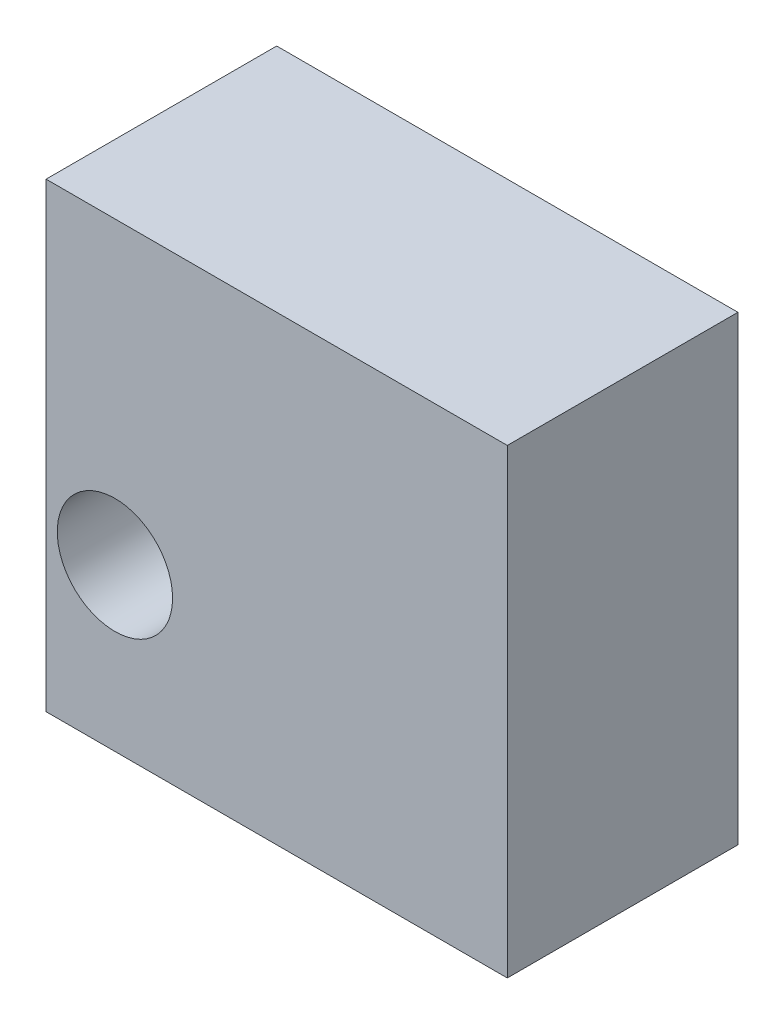
SolidWorks part; units mm, degrees
ref_plane "前视基准面" through (0, 0, 0) normal (0, 0, 1) x (1, 0, 0)
ref_plane "上视基准面" through (0, 0, 0) normal (0, 1, 0) x (1, 0, 0)
ref_plane "右视基准面" through (0, 0, 0) normal (1, 0, 0) x (0, 0, -1)
other "Configuration Table"
sketch "草图1" plane through (0, 0, 0) normal (0, 0, 1) x (1, 0, 0)
  line L1 (0, 0) -> (20, 0)
  line L2 (0, 0) -> (0, 20)
  line L3 (0, 20) -> (20, 20)
  line L4 (20, 0) -> (20, 20)
extrude "BaseBox" add sketch "草图1" along normal blind 10
hole_wizard "孔1" positions "草图3" profile "草图2" legacy
sketch "草图3" plane through (0, 0, 10) normal (0, 0, 1) x (1, 0, 0)
  point P0 (2.9854, 7.0052)
sketch "草图2" plane through (2.9854, 7.0052, 10) normal (1, 0, 0) x (0, -1, 0)
  line L0 (0, 0) -> (0, 10)
  line L1 (0, 10) -> (2.5, 10)
  line L2 (2.5, 10) -> (2.5, 0)
  line L3 (2.5, 0) -> (0, 0)
  line L4 (0, 110) -> (0, -10) construction
  dimension "直径" = 5
  dimension "深度" = 10
